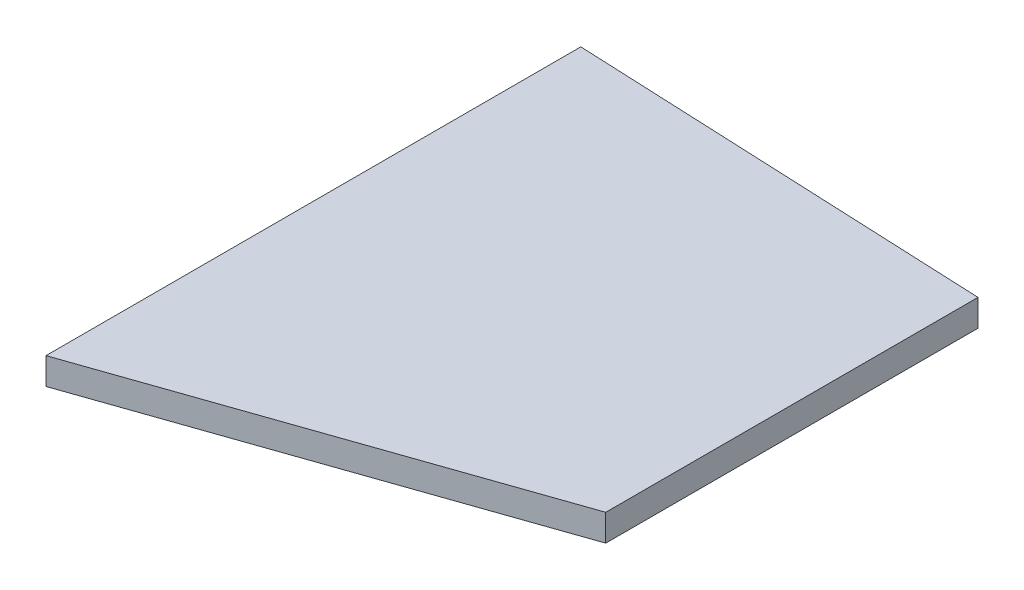
SolidWorks part; units mm, degrees
ref_plane "Front Plane" through (0, 0, 0) normal (0, 0, 1) x (1, 0, 0)
ref_plane "Top Plane" through (0, 0, 0) normal (0, 1, 0) x (1, 0, 0)
ref_plane "Right Plane" through (0, 0, 0) normal (1, 0, 0) x (0, 0, -1)
sketch "Sketch1" plane through (0, 0, 0) normal (0, 1, 0) x (1, 0, 0)
  line L1 (107.95, 0) -> (196.7632, 30.8151)
  line L3 (107.95, 114.3) -> (196.7632, 110.3723)
  line L4 (196.7632, 110.3723) -> (196.7632, 30.8151)
  line L5 (107.95, 114.3) -> (107.95, 0)
  line L7 (107.95, 114.3) -> (107.95, 0)
  line L9 (107.95, 104.1138) -> (107.95, 91.6704)
  line L13 (107.95, 79.8159) -> (107.95, 67.9614)
  line L17 (107.95, 54.217) -> (107.95, 43.737)
  line L21 (107.95, 28.2745) -> (107.95, 16.7636)
  dimension "D2" = 88.9
  dimension "D3" = 114.3
extrude "Boss-Extrude1" add sketch "Sketch1" along normal blind 5.715
